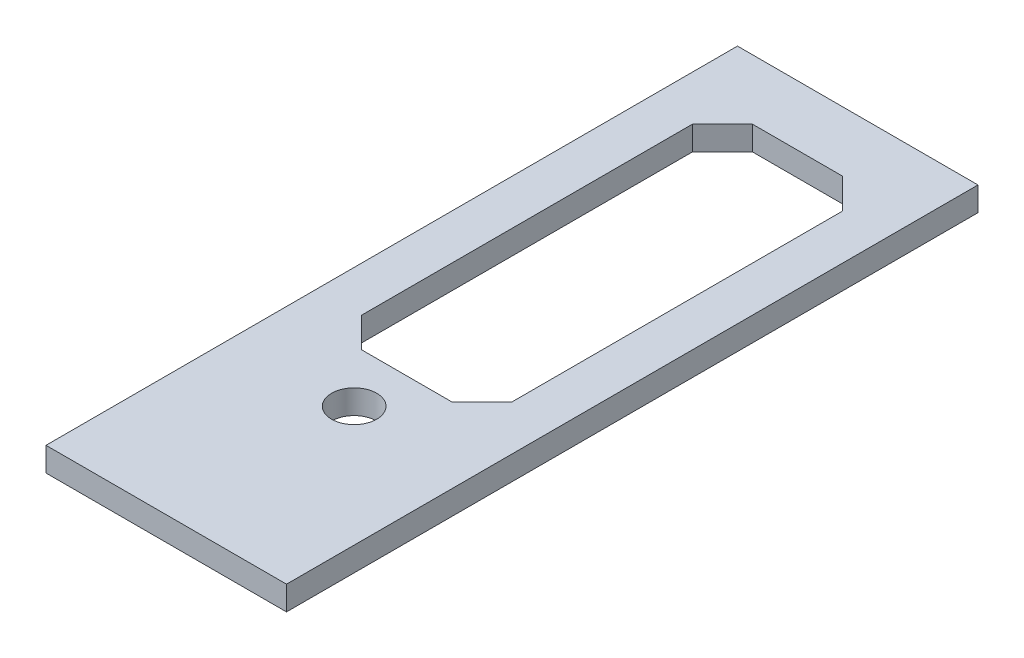
SolidWorks part; units mm, degrees
ref_plane "Front Plane" through (0, 0, 0) normal (0, 0, 1) x (1, 0, 0)
ref_plane "Top Plane" through (0, 0, 0) normal (0, 1, 0) x (1, 0, 0)
ref_plane "Right Plane" through (0, 0, 0) normal (1, 0, 0) x (0, 0, -1)
sketch "Sketch1" plane through (0, 0, 0) normal (0, 1, 0) x (1, 0, 0)
  line L1 (-8, -23) -> (8, -23)
  line L2 (-8, -23) -> (-8, 23)
  line L3 (-8, 23) -> (8, 23)
  line L4 (8, -23) -> (8, 23)
  line L5 (-8, -23) -> (8, 23) construction
  line L6 (-8, 23) -> (8, -23) construction
  point P0 (0, 0)
  dimension "D1" = 16
  dimension "D2" = 46
extrude "Boss-Extrude1" add sketch "Sketch1" along normal blind 1.6
sketch "Sketch3" plane through (0, 1.6, 0) normal (0, 1, 0) x (1, 0, 0)
  line L0 (8, 23) -> (-8, 23) construction
  line L1 (-5, 19) -> (5, 19)
  line L2 (-5, 19) -> (-5, -7)
  line L3 (-5, -7) -> (5, -7)
  line L4 (5, 19) -> (5, -7)
  line L5 (8, -23) -> (8, 23) construction
  line L6 (-8, 23) -> (-8, -23) construction
  line L7 (-8, -23) -> (8, -23) construction
  dimension "D1" = 4
  dimension "D2" = 3
  dimension "D3" = 3
  dimension "D4" = 16
extrude "Cut-Extrude2" cut sketch "Sketch3" against normal up to surface (1.6 mm away) up to face at (0, 0, 0)
chamfer "Chamfer2" distance 2 angle 45 4 edges at (5, 0.8, -19) (5, 0.8, 7) (-5, 0.8, 7) (-5, 0.8, -19)
sketch "Sketch4" plane through (0, 1.6, 0) normal (0, 1, 0) x (1, 0, 0)
  line L1 (-3, -7) -> (3, -7) construction
  circle A0 centre (0, -10.5) radius 1.5
  dimension "D1" = 3
  dimension "D2" = 3.5
extrude "Cut-Extrude3" cut sketch "Sketch4" against normal up to surface (1.6 mm away) up to face at (0, 0, -6)
